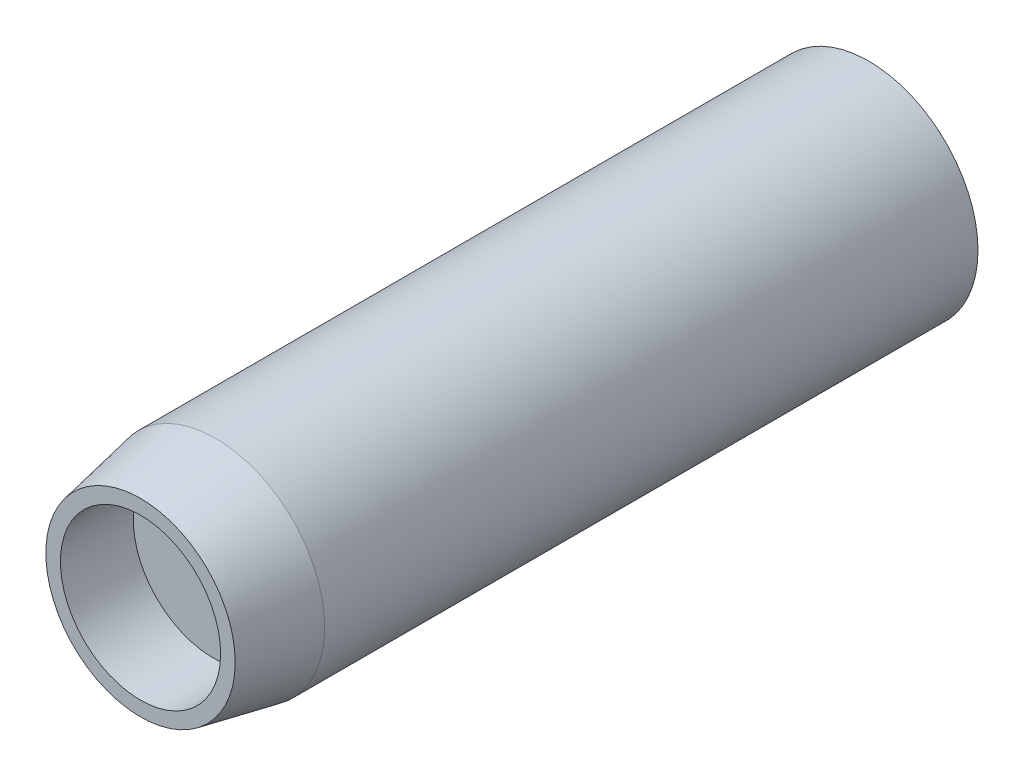
SolidWorks part; units mm, degrees
ref_plane "Front Plane" through (0, 0, 0) normal (0, 0, 1) x (1, 0, 0)
ref_plane "Top Plane" through (0, 0, 0) normal (0, 1, 0) x (1, 0, 0)
ref_plane "Right Plane" through (0, 0, 0) normal (1, 0, 0) x (0, 0, -1)
sketch "Sketch1" plane through (0, 0, 0) normal (0, 0, 1) x (1, 0, 0)
  circle A0 centre (0, 0) radius 7.5
  dimension "D1" = 15
extrude "Boss-Extrude1" add sketch "Sketch1" along normal blind 50
sketch "Sketch2" plane through (0, 0, 50) normal (0, 0, 1) x (1, 0, 0)
  circle A0 centre (0, 0) radius 5.5
  dimension "D1" = 11
extrude "Cut-Extrude1" cut sketch "Sketch2" against normal blind 5
chamfer "Chamfer1" distance 1 angle 79 1 edges at (7.5, 0, 50)
